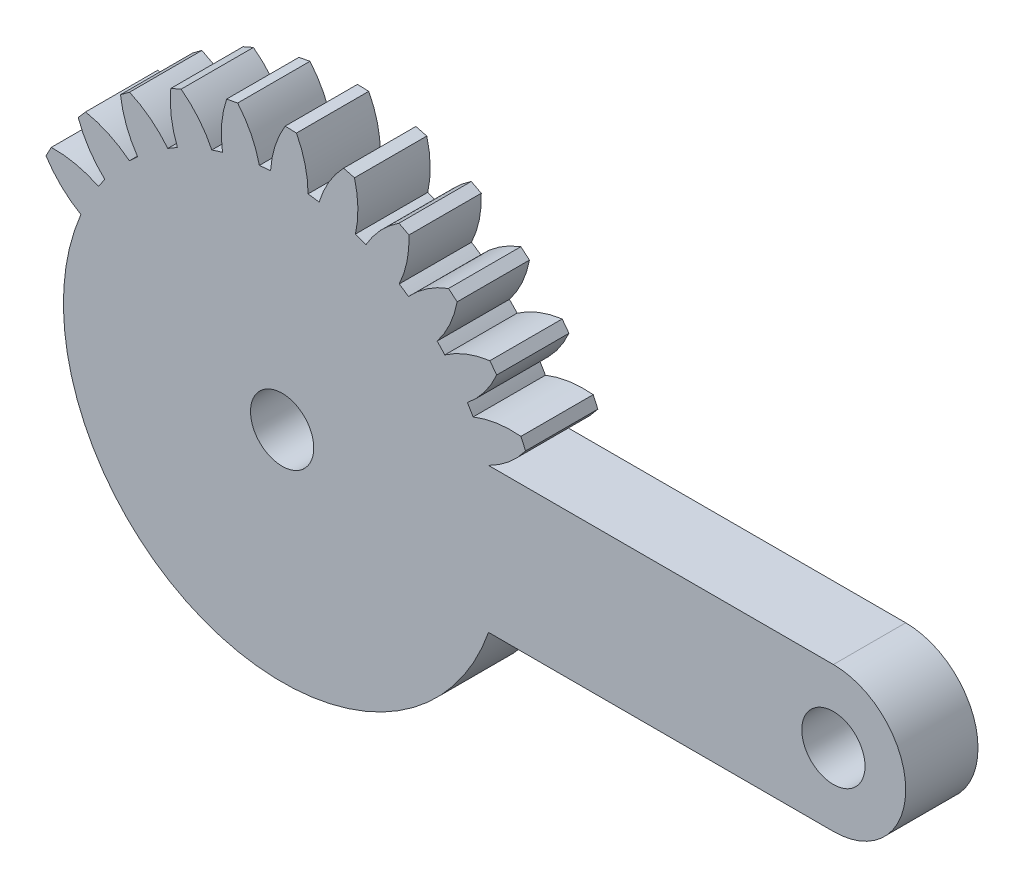
SolidWorks part; units mm, degrees
ref_plane "Front Plane" through (0, 0, 0) normal (0, 0, 1) x (1, 0, 0)
ref_plane "Top Plane" through (0, 0, 0) normal (0, 1, 0) x (1, 0, 0)
ref_plane "Right Plane" through (0, 0, 0) normal (1, 0, 0) x (0, 0, -1)
sketch "Sketch1" plane through (0, 0, 0) normal (0, 0, 1) x (1, 0, 0)
  line L0 (0, -1.75) -> (30.5, -1.75) construction
  line L1 (0, 1.75) -> (30.5, 1.75) construction
  line L2 (30.5, 1.75) -> (30.5, -1.75) construction
  line L3 (30.5, 4) -> (11.4197, 4)
  line L4 (30.5, -4) -> (11.4197, -4)
  line L5 (10.5671, 5.8946) -> (11.4197, 4) construction
  line L6 (13.2123, 6.288) -> (13.4684, 5.7189)
  line L7 (13.2123, 6.288) -> (10.8653, 5.2319) construction
  line L8 (13.4684, 5.7189) -> (11.1215, 4.6627) construction
  line L9 (11.4944, 9.0544) -> (11.8701, 8.556)
  line L10 (11.4944, 9.0544) -> (9.4392, 7.5054) construction
  line L11 (11.8701, 8.556) -> (9.8148, 7.0069) construction
  line L12 (9.2072, 11.3724) -> (9.6838, 10.9694)
  line L13 (9.2072, 11.3724) -> (7.5455, 9.4071) construction
  line L14 (9.6838, 10.9694) -> (8.0221, 9.0041) construction
  line L15 (6.4641, 13.127) -> (7.018, 12.8394)
  line L16 (6.4641, 13.127) -> (5.2781, 10.843) construction
  line L17 (7.018, 12.8394) -> (5.8321, 10.5553) construction
  line L18 (3.4007, 14.2316) -> (4.0046, 14.0736)
  line L19 (3.4007, 14.2316) -> (2.7493, 11.7418) construction
  line L20 (4.0046, 14.0736) -> (3.3532, 11.5838) construction
  line L21 (0.169, 14.6313) -> (0.7928, 14.6108)
  line L22 (0.169, 14.6313) -> (0.0844, 12.0591) construction
  line L23 (0.7928, 14.6108) -> (0.7082, 12.0386) construction
  line L24 (-3.0711, 14.3064) -> (-2.4582, 14.4243)
  line L25 (-3.0711, 14.3064) -> (-2.5847, 11.7791) construction
  line L26 (-2.4582, 14.4243) -> (-1.9718, 11.8971) construction
  line L27 (-6.1591, 13.2729) -> (-5.5875, 13.5234)
  line L28 (-6.1591, 13.2729) -> (-5.1259, 10.9158) construction
  line L29 (-5.5875, 13.5234) -> (-4.5542, 11.1663) construction
  line L30 (-8.9421, 11.582) -> (-8.44, 11.9528)
  line L31 (-8.9421, 11.582) -> (-7.4131, 9.5118) construction
  line L32 (-8.44, 11.9528) -> (-6.9111, 9.8826) construction
  line L33 (-11.2822, 9.3175) -> (-10.8746, 9.7901)
  line L34 (-11.2822, 9.3175) -> (-9.3332, 7.6367) construction
  line L35 (-10.8746, 9.7901) -> (-8.9256, 8.1094) construction
  line L36 (-13.0635, 6.5915) -> (-12.7705, 7.1426)
  line L37 (-13.0635, 6.5915) -> (-10.7911, 5.3834) construction
  line L38 (-12.7705, 7.1426) -> (-10.4981, 5.9345) construction
  line L39 (-11.1322, 4.7418) -> (11.4197, 4) construction
  arc A0 (11.4197, 4) -> (11.4197, -4) centre (0, 0) ccw
  circle A1 centre (0, 0) radius 1.75
  circle A2 centre (30.5, 0) radius 1.75
  arc A3 (30.5, -4) -> (30.5, 4) centre (30.5, 0) ccw
  arc A4 (10.5671, 5.8946) -> (13.2123, 6.288) centre (12.7001, 0.6432) cw
  arc A5 (13.4684, 5.7189) -> (11.4197, 4) centre (8.9365, 9.04) cw
  arc A6 (9.0018, 8.0857) -> (11.4944, 9.0544) centre (12.2434, 3.4361) cw
  arc A7 (11.8701, 8.556) -> (10.2523, 6.4266) centre (6.7159, 10.7926) cw
  arc A8 (6.9906, 9.8763) -> (9.2072, 11.3724) centre (11.1802, 6.0588) cw
  arc A9 (9.6838, 10.9694) -> (8.577, 8.5349) centre (4.1626, 12.0106) cw
  arc A10 (4.6332, 11.1778) -> (6.4641, 13.127) centre (9.5634, 8.3815) cw
  arc A11 (7.018, 12.8394) -> (6.477, 10.2205) centre (1.4032, 12.6338) cw
  arc A12 (2.0463, 11.9257) -> (3.4007, 14.2316) centre (7.4729, 10.289) cw
  arc A13 (4.0046, 14.0736) -> (4.0562, 11.3999) centre (-1.4257, 12.6313) cw
  arc A14 (-0.6419, 12.083) -> (0.169, 14.6313) centre (5.0122, 11.6869) cw
  arc A15 (0.7928, 14.6108) -> (1.4345, 12.0147) centre (-4.184, 12.0032) cw
  arc A16 (-3.2983, 11.6418) -> (-3.0711, 14.3064) centre (2.3034, 12.506) cw
  arc A17 (-2.4582, 14.4243) -> (-1.2582, 12.0344) centre (-6.7351, 10.7806) cw
  arc A18 (-5.7914, 10.624) -> (-6.1591, 13.2729) centre (-0.5196, 12.7058) cw
  arc A19 (-5.5875, 13.5234) -> (-3.8886, 11.4581) centre (-8.9526, 9.0241) cw
  arc A20 (-7.9977, 9.0801) -> (-8.9421, 11.582) centre (-3.3168, 12.2762) cw
  arc A21 (-8.44, 11.9528) -> (-6.3265, 10.3143) centre (-10.7267, 6.8206) cw
  arc A22 (-9.8078, 7.0864) -> (-11.2822, 9.3175) centre (-5.9497, 11.2387) cw
  arc A23 (-10.8746, 9.7901) -> (-8.451, 8.6597) centre (-11.9695, 4.2793) cw
  arc A24 (-11.1322, 4.7418) -> (-13.0635, 6.5915) centre (-8.288, 9.6445) cw
  arc A25 (-12.7705, 7.1426) -> (-10.1569, 6.5762) centre (-12.6196, 1.5261) cw
  point P103 (0, 0)
  dimension "D1" = 24.2
  dimension "D2" = 3.5
  dimension "D4" = 8
  dimension "D7" = 5.668
  dimension "D8" = 5.6185
  dimension "D3" = 30.5
  dimension "D5" = 0.6241
  dimension "D6" = 2.6742
  dimension "D9" = 2.6742
  dimension "D10" = 2.0776
  dimension "D11" = 89.999
  dimension "D12" = 11
  dimension "D13" = 22.5519
extrude "Boss-Extrude2" add sketch "Sketch1" along normal blind 4 contours L4 A3 L3 A0 A1 A2 | A13 L18 A12 A0 | A15 L21 A14 A0 | A17 L24 A16 A0 | A19 L27 A18 A0 | A21 L30 A20 A0 | A23 L33 A22 A0 | A25 L36 A24 A0 | A11 L15 A10 A0 | A9 L12 A8 A0 | A7 L9 A6 A0 | A5 L6 A4 A0
ref_point "Point1"
ref_point "Point2"
